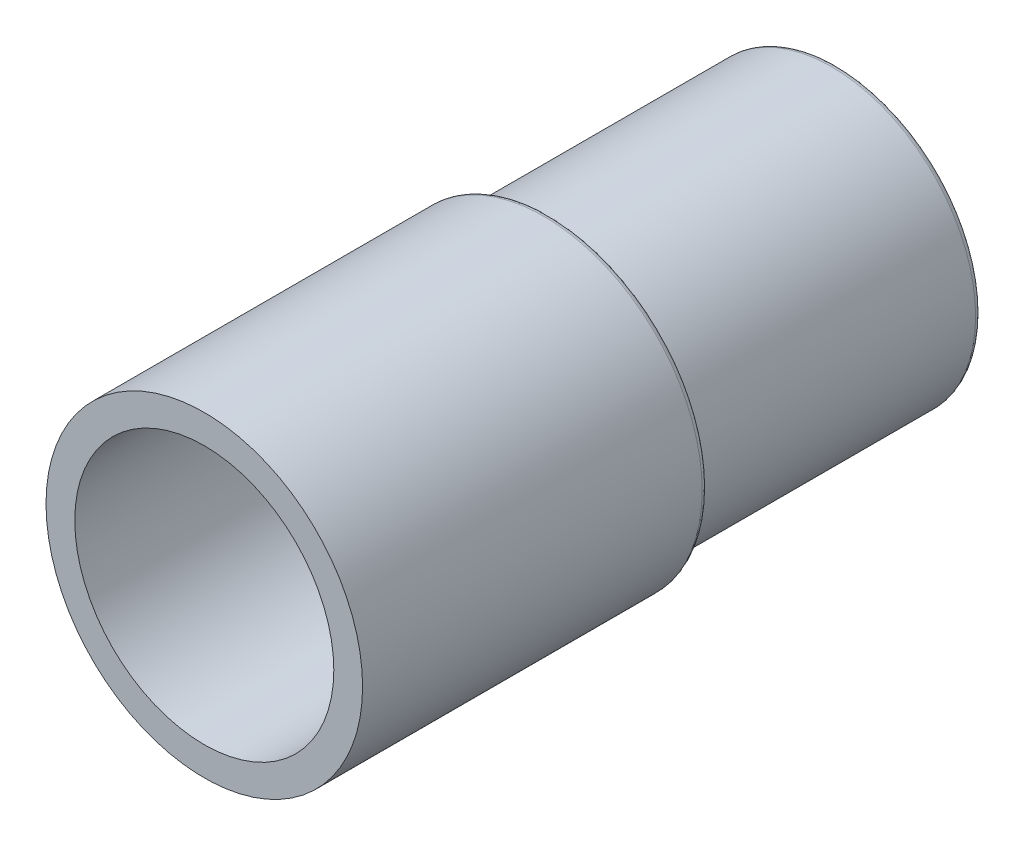
SolidWorks part; units mm, degrees
ref_plane "Спереди" through (0, 0, 0) normal (0, 0, 1) x (1, 0, 0)
ref_plane "Сверху" through (0, 0, 0) normal (0, 1, 0) x (1, 0, 0)
ref_plane "Справа" through (0, 0, 0) normal (1, 0, 0) x (0, 0, -1)
sketch "Эскиз1" plane through (0, 0, 0) normal (0, 0, 1) x (1, 0, 0)
  circle A0 centre (0, 0) radius 2
  circle A1 centre (0, 0) radius 2.5
  dimension "D1" = 4
  dimension "D2" = 5
extrude "Вытянуть1" add sketch "Эскиз1" along normal blind 5
sketch "Эскиз2" plane through (0, 0, 5) normal (0, 0, 1) x (1, 0, 0)
  circle A0 centre (0, 0) radius 2.25
  circle A1 centre (0, 0) radius 2.75
  dimension "D1" = 4.5
  dimension "D2" = 5.5
extrude "Вытянуть2" add sketch "Эскиз2" along normal blind 6
fillet "Скругление1" radius 0.1
